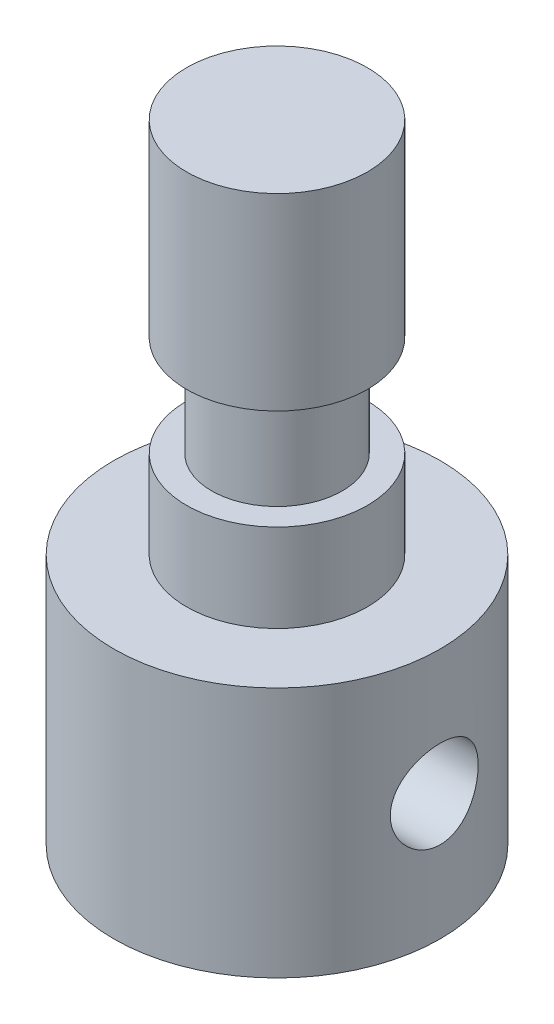
SolidWorks part; units mm, degrees
ref_plane "Front Plane" through (0, 0, 0) normal (0, 0, 1) x (1, 0, 0)
ref_plane "Top Plane" through (0, 0, 0) normal (0, 1, 0) x (1, 0, 0)
ref_plane "Right Plane" through (0, 0, 0) normal (1, 0, 0) x (0, 0, -1)
sketch "Sketch1" plane through (0, 0, 0) normal (0, 0, 1) x (1, 0, 0)
  line L0 (0, 0) -> (-6.5, 0)
  line L1 (-6.5, 0) -> (-6.5, 10)
  line L2 (-6.5, 10) -> (-3.6, 10)
  line L3 (-3.6, 10) -> (-3.6, 13.5)
  line L4 (-3.6, 25) -> (0, 25)
  line L5 (0, 25) -> (0, 0)
  line L6 (-3.6, 17.5) -> (-3.6, 25)
  line L7 (-3.6, 17.5) -> (-2.6, 17.5)
  line L9 (-3.6, 13.5) -> (-2.6, 13.5)
  line L10 (-2.6, 17.5) -> (-2.6, 13.5)
  dimension "D1" = 3.6
  dimension "D2" = 6.5
  dimension "D3" = 10
  dimension "D4" = 15
  dimension "D5" = 1
  dimension "D6" = 4
  dimension "D7" = 3.5
revolve "Revolve1" add sketch "Sketch1" angle 360 about L5
sketch "Sketch2" plane through (0, 0, 0) normal (1, 0, 0) x (0, 0, -1)
  line L0 (6.5, 10) -> (-6.5, 10) construction
  circle A0 centre (0, 5) radius 1.75
  dimension "D1" = 3.5
  dimension "D2" = 5
extrude "Cut-Extrude1" cut sketch "Sketch2" against normal through all both and the other way through all
